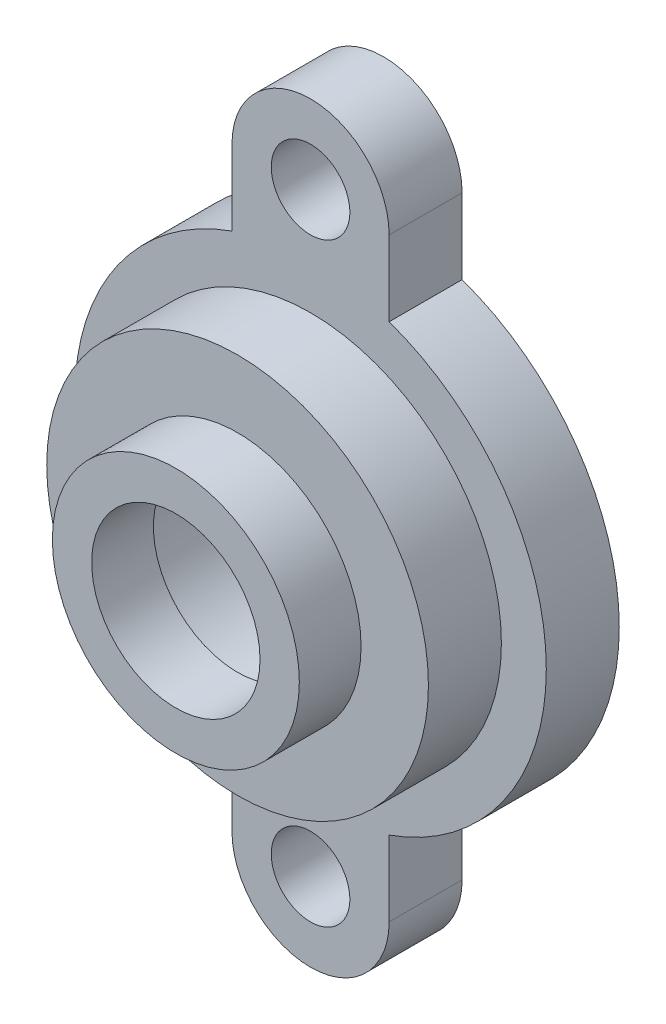
SolidWorks part; units mm, degrees
ref_plane "前视基准面" through (0, 0, 0) normal (0, 0, 1) x (1, 0, 0)
ref_plane "上视基准面" through (0, 0, 0) normal (0, 1, 0) x (1, 0, 0)
ref_plane "右视基准面" through (0, 0, 0) normal (1, 0, 0) x (0, 0, -1)
other "Configuration Table"
sketch "草图1" plane through (0, 0, 0) normal (0, 0, 1) x (1, 0, 0)
  circle A0 centre (0, 0) radius 21
extrude "凸台-拉伸2" add sketch "草图1" along normal blind 6.5
sketch "草图2" plane through (0, 0, 0) normal (0, 0, 1) x (1, 0, 0)
  line L0 (0, -26.5) -> (0, 26.5) construction
  line L1 (-7, -26.5) -> (-7, 26.5)
  line L2 (7, -26.5) -> (7, 26.5)
  arc A0 (-7, -26.5) -> (7, -26.5) centre (0, -26.5) ccw
  arc A1 (7, 26.5) -> (-7, 26.5) centre (0, 26.5) ccw
  point P3 (0, 0)
  point P8 (0, 0)
extrude "凸台-拉伸4" add sketch "草图2" along normal blind 6.5
sketch "草图3" plane through (0, 0, 0) normal (0, 0, 1) x (1, 0, 0)
  circle A0 centre (0, 0) radius 9.5
  circle A1 centre (0, -26.5) radius 3.5
  circle A2 centre (0, 26.5) radius 3.5
extrude "切除-拉伸1" cut sketch "草图3" along normal through all
sketch "草图4" plane through (0, 0, 0) normal (1, 0, 0) x (0, 0, -1)
  line L0 (-23.5, 0) -> (5, 0) construction
  line L1 (0, 9.5) -> (0, 17)
  line L2 (0, 17) -> (-13, 17)
  line L3 (-13, 17) -> (-13, 11)
  line L4 (-13, 11) -> (-18.5, 11)
  line L5 (-18.5, 11) -> (-18.5, 7.5)
  line L6 (-18.5, 7.5) -> (-13, 7.5)
  line L7 (-13, 7.5) -> (-13, 9.5)
  line L8 (-13, 9.5) -> (0, 9.5)
revolve "旋转1" add sketch "草图4" angle 360 about L0
